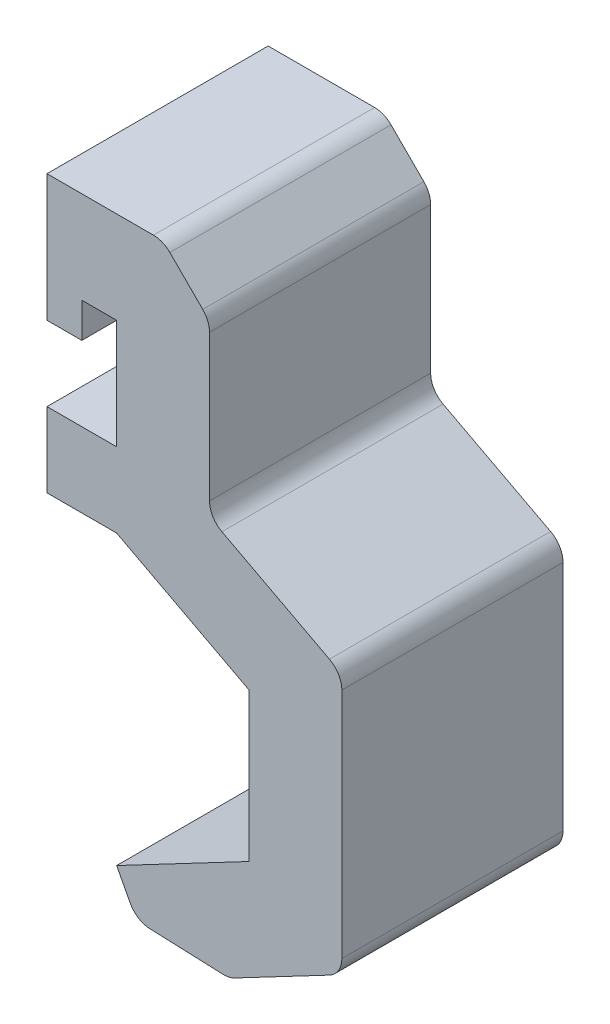
SolidWorks part; units mm, degrees
ref_plane "前基準面" through (0, 0, 0) normal (0, 0, 1) x (1, 0, 0)
ref_plane "上基準面" through (0, 0, 0) normal (0, 1, 0) x (1, 0, 0)
ref_plane "右基準面" through (0, 0, 0) normal (1, 0, 0) x (0, 0, -1)
sketch "Sketch2" plane through (0, 0, 0) normal (0, 0, 1) x (1, 0, 0)
  line L0 (0, 6.4475) -> (0, 12.6475) construction
  line L1 (0, 12.6475) -> (22.5, 12.6475) construction
  line L2 (22.5, 12.6475) -> (25.35, 11.1475)
  line L3 (25.35, 11.1475) -> (25.35, 7.9475)
  line L4 (25.35, 7.9475) -> (22.5, 6.4475)
  line L5 (22.5, 6.4475) -> (0, 6.4475) construction
  line L6 (0, 9.5475) -> (25.35, 9.5475) construction
  line L7 (22.5, 18.6006) -> (24.5, 18.6006)
  line L8 (22.5, 12.6475) -> (0, 12.6475) construction
  line L9 (21, 14.2569) -> (21, 12.6475)
  line L11 (0, 12.6475) -> (0, 16.6162) construction
  line L12 (21, 14.2569) -> (22.5, 14.2569)
  line L13 (22.5, 16.6162) -> (22.5, 18.6006) construction
  line L14 (22.5, 18.6006) -> (21, 18.6006)
  line L15 (21, 16.6162) -> (21, 18.6006)
  line L16 (24.5, 18.6006) -> (24.5, 13.9469)
  line L17 (24.5, 13.9469) -> (27.35, 12.4469)
  line L18 (27.35, 12.4469) -> (27.35, 6.8356)
  line L19 (27.35, 6.8356) -> (23.3921, 4.7525)
  line L20 (23.3921, 4.7525) -> (22.5, 6.4475)
  line L21 (21, 16.6162) -> (0, 16.6162) construction
  line L22 (22.5, 14.2569) -> (22.5, 16.6162)
  line L23 (21, 16.6162) -> (21, 15.8662)
  line L24 (21, 15.8662) -> (21.75, 15.8662)
  line L25 (21.75, 16.6162) -> (21.75, 15.8662)
  line L26 (22.5, 12.6475) -> (21, 12.6475)
  line L27 (22.5, 16.6162) -> (21.75, 16.6162)
  dimension "D1" = 6.2
  dimension "D2" = 3.2
  dimension "D3" = 22.5
  dimension "D4" = 25.35
  dimension "D5" = 3.9688
  dimension "D6" = 1.9844
  dimension "D7" = 1.5
  dimension "D8" = 2
  dimension "D9" = 2
  dimension "D10" = 0.75
  dimension "D11" = 0.75
  dimension "D13" = 1.5
extrude "Boss-Extrude1" add sketch "Sketch2" along normal blind 4.7625
chamfer "Chamfer1" distance 1 angle 45 1 edges at (24.5, 18.6006, 2.3813)
fillet "Fillet1" radius 0.5 5 edges at (27.35, 6.8356, 2.3813) (27.35, 12.4469, 2.3813) (24.5, 13.9469, 2.3813) (24.5, 17.6006, 2.3813) (23.5, 18.6006, 2.3813)
chamfer "Chamfer2" distance 1 angle 60 1 edges at (23.3921, 4.7525, 2.3813)
fillet "Fillet2" radius 0.5 2 edges at (22.9263, 5.6375, 2.3813) (24.9248, 5.5592, 2.3813)
